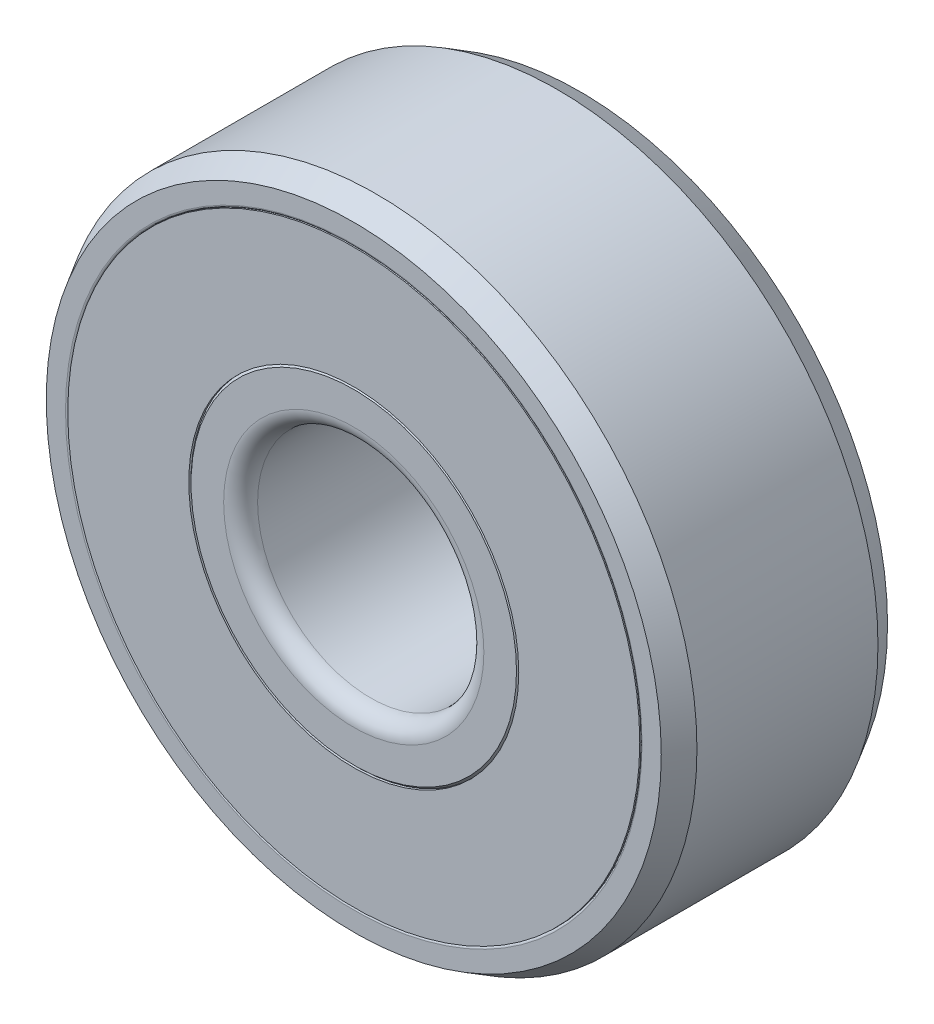
SolidWorks part; units mm, degrees
ref_plane "Front Plane" through (0, 0, 0) normal (0, 0, 1) x (1, 0, 0)
ref_plane "Top Plane" through (0, 0, 0) normal (0, 1, 0) x (1, 0, 0)
ref_plane "Right Plane" through (0, 0, 0) normal (1, 0, 0) x (0, 0, -1)
sketch "Sketch1" plane through (0, 0, 0) normal (0, 0, 1) x (1, 0, 0)
  line L0 (0, 5.75) -> (0, 8.5) construction
  line L1 (0, 3) -> (0, 5.75) construction
  line L2 (0, 8.5) -> (0, 7.5833) construction
  line L3 (0, 7.5833) -> (0, 6.6667) construction
  line L4 (0, 6.6667) -> (0, 5.75) construction
  circle A0 centre (0, 0) radius 3
  circle A1 centre (0, 0) radius 8.5
  circle A2 centre (0, 0) radius 7.5833 construction
  circle A4 centre (0, 0) radius 4.375 construction
  point P6 (0, 4.375)
  dimension "OD" = 17
  dimension "ID" = 6
sketch "Sketch2" plane through (0, 0, 0) normal (1, 0, 0) x (0, 0, -1)
  line L0 (-3, 8.5) -> (3, 8.5) construction
  line L1 (3, 8.5) -> (3, -8.5) construction
  line L2 (3, 0) -> (-3, 0) construction
  line L3 (-3, 3) -> (-3, -3) construction
  point P2 (0, 8.5)
  dimension "Width" = 6
  dimension "For Shaft Diameter" = 6
  dimension "For Housing ID" = 17
sketch "Sketch3" plane through (0, 0, 0) normal (1, 0, 0) x (0, 0, -1)
  line L0 (-2.4, -8.5) -> (2.4, -8.5)
  line L3 (-3, -7.6433) -> (-3, -8.1536)
  line L4 (0, -4.375) -> (0, -7.5833) construction
  line L5 (-2.4, -8.5) -> (-3, -8.1536)
  line L6 (-2.55, -3) -> (2.55, -3)
  line L7 (-1.5278, -7.5833) -> (-1.5278, -7.8889) construction
  line L8 (-2.94, -4.375) -> (-1.5278, -4.375)
  line L9 (-3, -4.375) -> (0, -4.375) construction
  line L11 (-3, -7.5833) -> (-3, -4.375) construction
  line L12 (-3, -4.315) -> (-3, -3.45)
  line L14 (-3, 0) -> (3, 0) construction
  line L15 (-2.94, -7.5833) -> (-1.5278, -7.5833)
  line L17 (0, 0) -> (0, -8.5) construction
  line L18 (-1.5278, -7.8889) -> (-1.5278, -8.1944) construction
  line L19 (2.4, -8.5) -> (3, -8.1536)
  line L20 (0, -7.5833) -> (-3, -7.5833) construction
  line L21 (-3, 3) -> (-3, -3) construction
  line L22 (-1.5278, -8.1944) -> (-1.5278, -8.5) construction
  line L30 (-3, -4.315) -> (-2.94, -4.375)
  line L31 (2.94, -4.375) -> (1.5278, -4.375)
  line L32 (3, -4.315) -> (2.94, -4.375)
  line L33 (3, -4.315) -> (3, -3.45)
  line L34 (2.94, -7.5833) -> (1.5278, -7.5833)
  line L35 (3, -7.6433) -> (3, -8.1536)
  line L36 (0, 8.5) -> (0, -8.5) construction
  arc A0 (0, -3.7639) -> (0, -8.1944) centre (0, -5.9792) ccw construction
  arc A1 (-1.5278, -4.375) -> (1.5278, -4.375) centre (0, -5.9792) cw
  arc A2 (-1.5278, -7.5833) -> (1.5278, -7.5833) centre (0, -5.9792) ccw
  arc A4 (-2.94, -7.5833) -> (-3, -7.6433) centre (-2.94, -7.6433) ccw
  arc A5 (-2.55, -3) -> (-3, -3.45) centre (-2.55, -3.45) ccw
  arc A6 (2.55, -3) -> (3, -3.45) centre (2.55, -3.45) cw
  arc A7 (2.94, -7.5833) -> (3, -7.6433) centre (2.94, -7.6433) cw
  point P28 (0, -5.9792)
  point P46 (-3, -3)
  point P54 (0, -3)
  dimension "D4" = 0.06
  dimension "D7" = 0.45
  dimension "D5" = 45
  dimension "D6" = 0.06
  dimension "D3" = 0.6
  dimension "D2" = 60
revolve "Revolve1" add sketch "Sketch3" angle 360 about L14
sketch "Sketch4" plane through (0, 0, 0) normal (1, 0, 0) x (0, 0, -1)
  line L0 (-2.94, -7.5833) -> (-1.5278, -7.5833) construction
  line L1 (-3, -4.375) -> (-2.4115, -4.375)
  line L2 (-3, -4.375) -> (-3, -7.5833)
  line L3 (-3, -7.5833) -> (-2.4115, -7.5833)
  line L4 (-2.4115, -4.375) -> (-2.4115, -7.5833)
  line L5 (-3, -4.315) -> (-3, -3.45) construction
  line L6 (-3, -5.9792) -> (-2.8038, -5.9792) construction
  line L7 (-2.8038, -5.9792) -> (-2.6076, -5.9792) construction
  line L8 (-2.6076, -5.9792) -> (-2.4115, -5.9792) construction
  line L9 (-2.4115, -5.9792) -> (-2.2153, -5.9792) construction
  line L10 (-3, -7.5833) -> (-3, -4.375) construction
  line L11 (-2.94, -4.375) -> (-1.5278, -4.375) construction
  arc A1 (0, -3.7639) -> (0, -8.1944) centre (0, -5.9792) ccw construction
revolve "Revolve2" add sketch "Sketch4" angle 360 about L14
sketch "Sketch5" plane through (0, 0, 0) normal (1, 0, 0) x (0, 0, -1)
  line L2 (0, -3.7639) -> (0, -8.1944)
  arc A2 (0, -8.1944) -> (0, -3.7639) centre (0, -5.9792) cw
revolve "Revolve3" add sketch "Sketch5" angle 360 about L17
pattern_circular "CirPattern1" count 7 over 360 about axis through (0, 0, 0) along (0, 0, 1) of bodies 138
equation "\"D4@Sketch3\"=\"Width@Sketch2\"*.01"
equation "\"D6@Sketch3\"=\"Width@Sketch2\"*.01"
equation "\"D7@Sketch3\"=\"Width@Sketch2\"*.075"
equation "\"D3@Sketch3\"=\"Width@Sketch2\"*.1"
